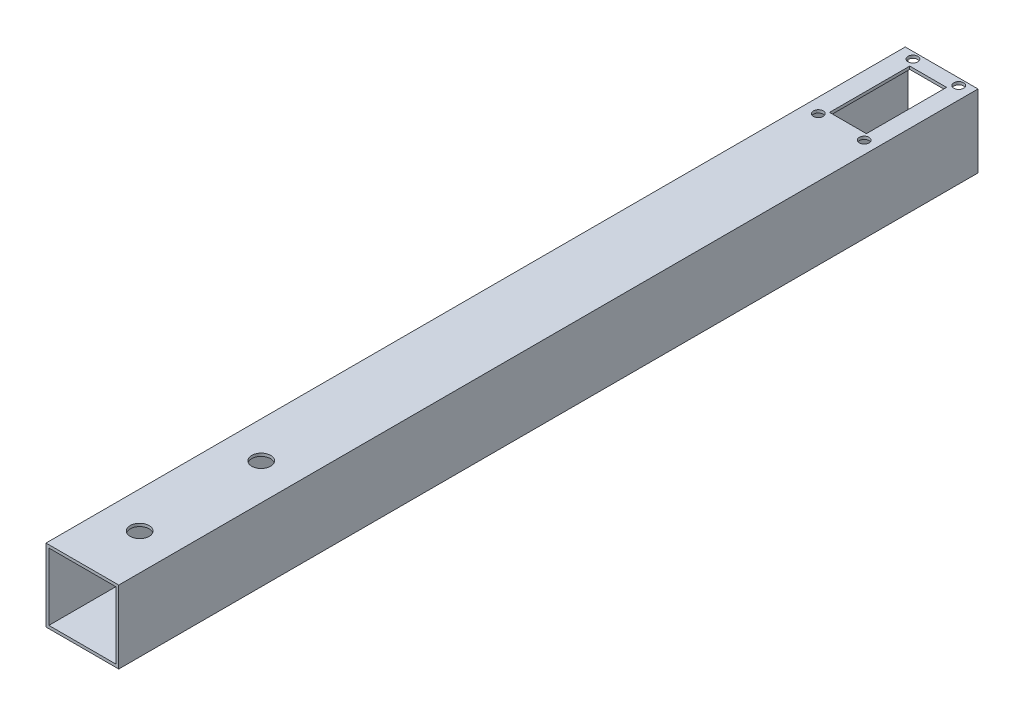
SolidWorks part; units mm, degrees
ref_plane "Front Plane" through (0, 0, 0) normal (0, 0, 1) x (1, 0, 0)
ref_plane "Top Plane" through (0, 0, 0) normal (0, 1, 0) x (1, 0, 0)
ref_plane "Right Plane" through (0, 0, 0) normal (1, 0, 0) x (0, 0, -1)
sketch "Sketch1" plane through (0, 0, 0) normal (0, 0, 1) x (1, 0, 0)
  line L1 (-12.7, 12.7) -> (12.7, 12.7)
  line L2 (-12.7, 12.7) -> (-12.7, -12.7)
  line L3 (-12.7, -12.7) -> (12.7, -12.7)
  line L4 (12.7, 12.7) -> (12.7, -12.7)
  line L5 (-12.7, 12.7) -> (12.7, -12.7) construction
  line L6 (-12.7, -12.7) -> (12.7, 12.7) construction
  line L11 (-5.2004, 5.2004) -> (10.6004, -10.6004) construction
  line L12 (-7.9004, -7.9004) -> (7.9004, 7.9004) construction
  line L13 (-11.7, 11.7) -> (11.7, 11.7)
  line L14 (-11.7, 11.7) -> (-11.7, -11.7)
  line L15 (-11.7, -11.7) -> (11.7, -11.7)
  line L16 (11.7, 11.7) -> (11.7, -11.7)
  line L17 (-11.7, 11.7) -> (11.7, -11.7) construction
  line L18 (-11.7, -11.7) -> (11.7, 11.7) construction
  point P0 (0, 0)
  point P6 (0, 0)
  point P12 (0, 0)
  dimension "D1" = 25.4
  dimension "D2" = 25.4
  dimension "D3" = 23.4
  dimension "D4" = 23.4
extrude "Boss-Extrude1" add sketch "Sketch1" along normal blind 300
hole_wizard "M6 Clearance Hole1" positions "Sketch2" profile "Sketch3" hole size "M6" standard "ISO"
sketch "Sketch2" plane through (0, 12.7, 0) normal (0, 1, 0) x (1, 0, 0)
  line L0 (12.7, -300) -> (-12.7, -300) construction
  point P0 (0, -280)
  point P2 (0, -237.57)
  dimension "D1" = 20
  dimension "D2" = 42.43
sketch "Sketch3" plane through (0, 12.7, 280) normal (1, 0, 0) x (0, 0, 1)
  line L0 (0, 0) -> (0, 11.9828)
  line L1 (0, 11.9828) -> (3.3, 10)
  line L2 (3.3, 10) -> (3.3, 0)
  line L5 (3.3, 0) -> (0, 0)
  line L10 (0, 11.9828) -> (-3.3, 10) construction
  line L11 (0, -6.35) -> (0, 107.95) construction
  dimension "Hole Dia." = 6.6
  dimension "Hole Depth" = 10
  dimension "Drill Angle" = 118
sketch "Sketch5" plane through (0, 12.7, 0) normal (0, 1, 0) x (1, 0, 0)
  line L1 (6.7306, -5) -> (-6.1306, -5)
  line L2 (6.7306, -5) -> (6.7306, -33)
  line L3 (6.7306, -33) -> (-6.1306, -33)
  line L4 (-6.1306, -5) -> (-6.1306, -33)
extrude "Cut-Extrude2" cut sketch "Sketch5" against normal blind 10
hole_wizard "M3 Clearance Hole1" positions "Sketch6" profile "Sketch7" hole size "M3" standard "ISO"
sketch "Sketch6" plane through (0, 12.7, 0) normal (0, 1, 0) x (1, 0, 0)
  point P0 (8.3, -2.32)
  point P3 (-7.7, -2.32)
  point P6 (-7.7, -35.3409)
  point P9 (8.3, -35.3409)
sketch "Sketch7" plane through (8.3, 12.7, 2.32) normal (1, 0, 0) x (0, 0, 1)
  line L0 (0, 0) -> (0, 11.0215)
  line L1 (0, 11.0215) -> (1.7, 10)
  line L2 (1.7, 10) -> (1.7, 0)
  line L5 (1.7, 0) -> (0, 0)
  line L10 (0, 11.0215) -> (-1.7, 10) construction
  line L11 (0, -6.35) -> (0, 107.95) construction
  dimension "Hole Dia." = 3.4
  dimension "Hole Depth" = 10
  dimension "Drill Angle" = 118
